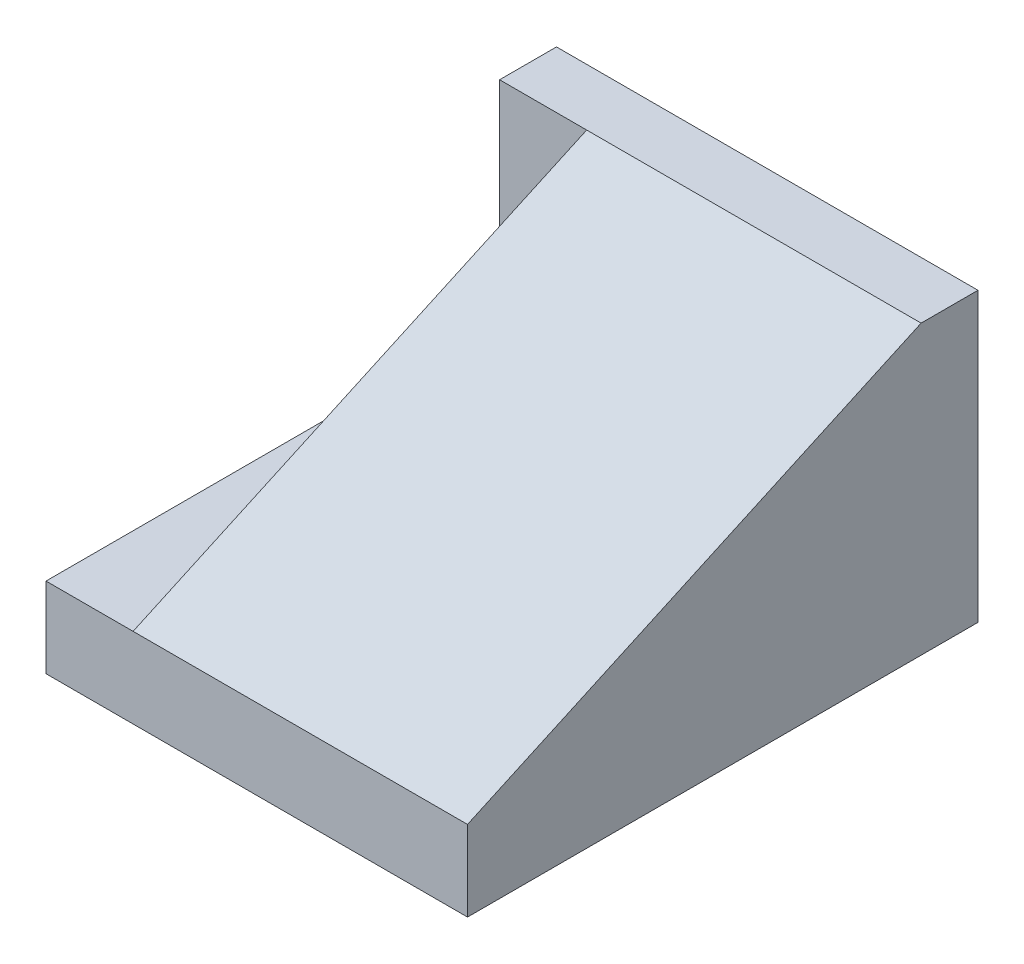
SolidWorks part; units mm, degrees
ref_plane "Front Plane" through (0, 0, 0) normal (0, 0, 1) x (1, 0, 0)
ref_plane "Top Plane" through (0, 0, 0) normal (0, 1, 0) x (1, 0, 0)
ref_plane "Right Plane" through (0, 0, 0) normal (1, 0, 0) x (0, 0, -1)
sketch "Sketch1" plane through (0, 0, 0) normal (0, 1, 0) x (1, 0, 0)
  line L1 (-63.0211, 76.321) -> (63.0211, 76.321)
  line L2 (-63.0211, 76.321) -> (-63.0211, -76.321)
  line L3 (-63.0211, -76.321) -> (63.0211, -76.321)
  line L4 (63.0211, 76.321) -> (63.0211, -76.321)
  line L5 (-63.0211, 76.321) -> (63.0211, -76.321) construction
  line L6 (-63.0211, -76.321) -> (63.0211, 76.321) construction
  point P0 (0, 0)
extrude "Boss-Extrude1" add sketch "Sketch1" along normal blind 24
sketch "Sketch2" plane through (0, 24, 0) normal (0, 1, 0) x (1, 0, 0)
  line L0 (63.0211, -76.321) -> (63.0211, 76.321) construction
  line L1 (-63.0211, 76.321) -> (63.0211, 76.321)
  line L2 (-63.0211, 76.321) -> (-63.0211, 59.3117)
  line L3 (-63.0211, 59.3117) -> (63.0211, 59.3117)
  line L4 (63.0211, 76.321) -> (63.0211, 59.3117)
extrude "Boss-Extrude2" add sketch "Sketch2" along normal blind 62
sketch "Sketch3" plane through (63.0211, 0, 0) normal (1, 0, 0) x (0, 0, -1)
  line L0 (59.3117, 86) -> (-76.321, 24)
rib "Rib1" sketch "Sketch3" sketch "Sketch3" thickness 100 extrusion direction parallel to sketch draft on no parameters "D1"=100
